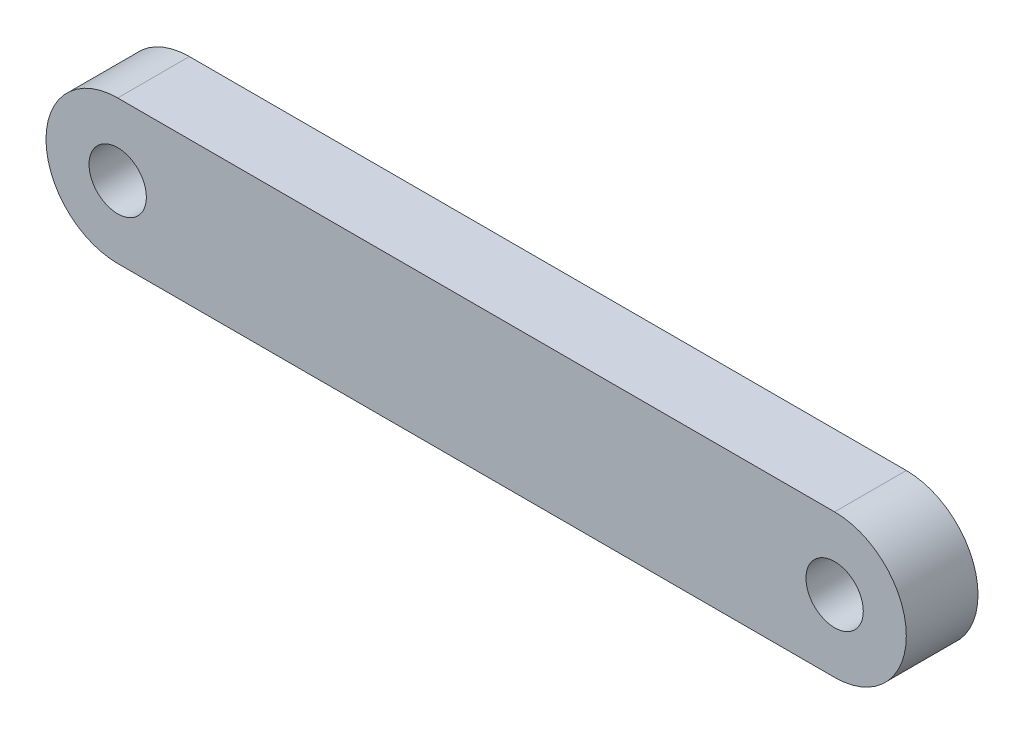
SolidWorks part; units mm, degrees
ref_plane "前基準面" through (0, 0, 0) normal (0, 0, 1) x (1, 0, 0)
ref_plane "上基準面" through (0, 0, 0) normal (0, 1, 0) x (1, 0, 0)
ref_plane "右基準面" through (0, 0, 0) normal (1, 0, 0) x (0, 0, -1)
sketch "草圖2" plane through (0, 0, 0) normal (0, 0, 1) x (1, 0, 0)
  line L0 (-25, 0) -> (25, 0) construction
  line L1 (-25, 5) -> (25, 5)
  line L2 (-25, -5) -> (25, -5)
  arc A0 (-25, 5) -> (-25, -5) centre (-25, 0) ccw
  arc A1 (25, -5) -> (25, 5) centre (25, 0) ccw
  circle A2 centre (25, 0) radius 2
  circle A3 centre (-25, 0) radius 2
  point P2 (0, 0)
  dimension "D2" = 4
  dimension "D3" = 5
  dimension "D1" = 50
extrude "填料-伸長1" add sketch "草圖2" along normal mid plane 5
